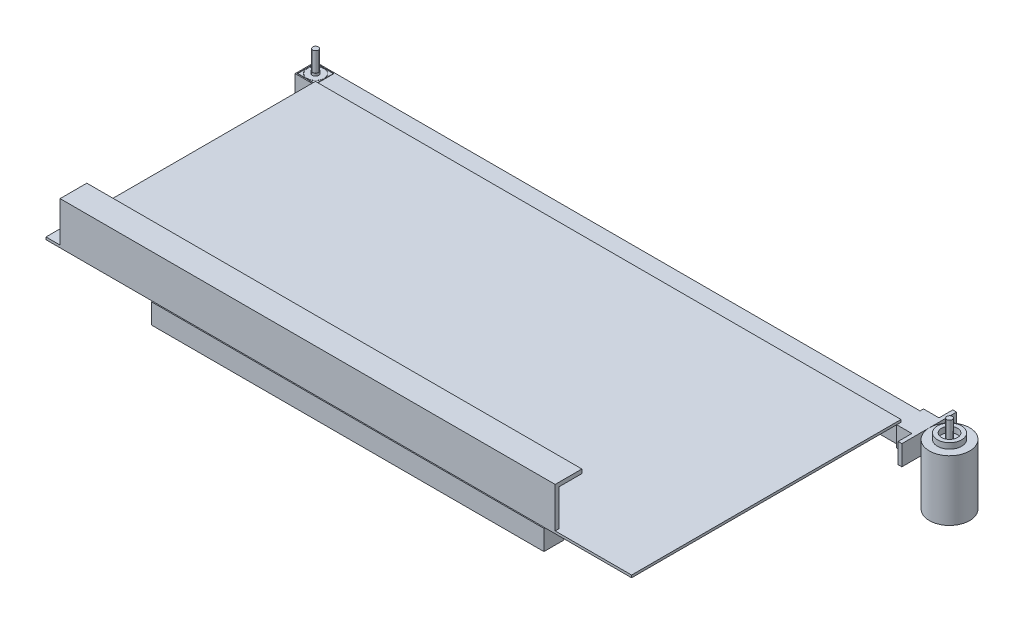
SolidWorks part; units mm, degrees
ref_plane "Front Plane" through (0, 0, 0) normal (0, 0, 1) x (1, 0, 0)
ref_plane "Top Plane" through (0, 0, 0) normal (0, 1, 0) x (1, 0, 0)
ref_plane "Right Plane" through (0, 0, 0) normal (1, 0, 0) x (0, 0, -1)
sketch "Sketch1" plane through (0, 0, 0) normal (0, 1, 0) x (1, 0, 0)
  line L0 (-360.5072, 0) -> (389.4928, 0)
  line L1 (389.4928, 0) -> (389.4928, -25)
  line L2 (389.4928, -25) -> (189.4928, -25)
  line L3 (189.4928, -25) -> (189.4928, -335)
  line L4 (189.4928, -335) -> (258.3333, -335)
  line L5 (258.3333, -335) -> (258.3333, -360)
  line L6 (258.3333, -360) -> (-229.3478, -360)
  line L7 (-229.3478, -360) -> (-229.3478, -335)
  line L8 (-229.3478, -335) -> (-160.5072, -335)
  line L9 (-160.5072, -335) -> (-160.5072, -25)
  line L10 (-160.5072, -25) -> (-360.5072, -25)
  line L11 (-360.5072, -25) -> (-360.5072, 0)
  line L12 (-135.5072, -25) -> (164.4928, -25)
  line L13 (164.4928, -25) -> (164.4928, -335)
  line L14 (164.4928, -335) -> (-135.5072, -335)
  line L15 (-135.5072, -335) -> (-135.5072, -25)
  dimension "D1" = 750
  dimension "D2" = 200
  dimension "D3" = 300
  dimension "D4" = 25
  dimension "D5" = 25
  dimension "D6" = 25
  dimension "D7" = 310
extrude "Boss-Extrude1" add sketch "Sketch1" along normal blind 25 contours L9 L10 L11 L0 L1 L2 L3 L4 L5 L6 L7 L8
sketch "Sketch4" plane through (-360.5072, 0, 0) normal (-1, 0, 0) x (0, 0, 1)
  line L1 (0, 25) -> (25.1974, 25)
  line L2 (0, 25) -> (0, -19.8582)
  line L3 (0, -19.8582) -> (25.1974, -19.8582)
  line L4 (25.1974, 25) -> (25.1974, -19.8582)
extrude "Boss-Extrude2" add sketch "Sketch4" along normal blind 25
sketch "Sketch5" plane through (0, 25, 0) normal (0, 1, 0) x (1, 0, 0)
  line L1 (-384.3095, -1.1004) -> (-361.3635, -1.1004)
  line L2 (-384.3095, -1.1004) -> (-384.3095, -23.8607)
  line L3 (-384.3095, -23.8607) -> (-361.3635, -23.8607)
  line L4 (-361.3635, -1.1004) -> (-361.3635, -23.8607)
extrude "Cut-Extrude1" cut sketch "Sketch5" against normal through all
sketch "Sketch7" plane through (0, 25, 0) normal (0, 1, 0) x (1, 0, 0)
  line L1 (-383.9453, -1.439) -> (-361.7536, -1.439)
  line L2 (-383.9453, -1.439) -> (-383.9453, -23.502)
  line L3 (-383.9453, -23.502) -> (-361.7536, -23.502)
  line L4 (-361.7536, -1.439) -> (-361.7536, -23.502)
extrude "Boss-Extrude4" add sketch "Sketch7" against normal blind 44 separate body
sketch "Sketch8" plane through (0, 25, 0) normal (0, 1, 0) x (1, 0, 0)
  line L0 (-384.3095, -1.1004) -> (-361.3635, -23.8607) construction
  circle A0 centre (-372.8365, -12.4805) radius 10.6558
extrude "Cut-Extrude2" cut sketch "Sketch8" against normal blind 8
sketch "Sketch9" plane through (0, -19, 0) normal (0, -1, 0) x (-1, 0, 0)
  line L0 (361.2767, -23.8809) -> (384.2478, -1.0919) construction
  circle A0 centre (372.7622, -12.4864) radius 10.6384
extrude "Cut-Extrude3" cut sketch "Sketch9" against normal blind 8
sketch "Sketch12" plane through (0, 17, 0) normal (0, 1, 0) x (1, 0, 0)
  line L0 (-361.3635, -1.1004) -> (-384.3095, -23.8607) construction
  circle A0 centre (-372.8365, -12.4805) radius 10.4586
  circle A1 centre (-372.8365, -12.4805) radius 4
  dimension "D1" = 8
extrude "Boss-Extrude5" add sketch "Sketch12" along normal through all and the other way through all
ref_plane "Plane1" through (0, 26, 0) normal (0, 1, 0) x (1, 0, 0)
sketch "Sketch14" plane through (0, 26, 0) normal (0, 1, 0) x (1, 0, 0)
  line L1 (-360.5072, -25) -> (366.97, -25)
  line L2 (-360.5072, -25) -> (-360.5072, -359.7131)
  line L3 (-360.5072, -359.7131) -> (366.97, -359.7131)
  line L4 (366.97, -25) -> (366.97, -359.7131)
extrude "Boss-Extrude6" add sketch "Sketch14" along normal blind 3 separate body
sketch "Sketch15" plane through (0, 0, 0) normal (1, 0, 0) x (0, 0, -1)
  line L0 (-359.7131, 29) -> (-359.7131, 79)
  line L1 (-359.7131, 79) -> (-326.5002, 79)
  line L2 (-326.5002, 79) -> (-326.5002, 74)
  line L3 (-326.5002, 74) -> (-354.7131, 74)
  line L4 (-354.7131, 74) -> (-354.7131, 29)
  line L5 (-354.7131, 29) -> (-359.7131, 29)
  dimension "D1" = 50
  dimension "D2" = 5
  dimension "D3" = 45
extrude "Boss-Extrude7" add sketch "Sketch15" along normal blind 272 and the other way blind 343
sketch "Sketch16" plane through (0, 25, 0) normal (0, 1, 0) x (1, 0, 0)
  circle A0 centre (-372.8365, -12.4805) radius 3.9261
extrude "Boss-Extrude8" add sketch "Sketch16" along normal blind 3 and the other way blind 54
sketch "Sketch17" plane through (0, 28, 0) normal (0, 1, 0) x (1, 0, 0)
  circle A2 centre (-372.8365, -12.4805) radius 3.45
  dimension "D1" = 6.9
extrude "Boss-Extrude9" add sketch "Sketch17" along normal blind 24
sketch "Sketch18" plane through (0, 25, 0) normal (0, 1, 0) x (1, 0, 0)
  line L0 (389.4928, -25) -> (389.4928, 0) construction
  circle A0 centre (414.4928, -12.2466) radius 25
  dimension "D1" = 50
extrude "Boss-Extrude10" add sketch "Sketch18" against normal blind 75 separate body
sketch "Sketch19" plane through (0, 25, 0) normal (0, 1, 0) x (1, 0, 0)
  line L0 (389.4928, 0) -> (389.4928, 21.4834)
  line L1 (389.4928, 21.4834) -> (384.8178, 21.4834)
  line L2 (384.8178, 21.4834) -> (384.8178, 4.3334)
  line L3 (384.8178, 4.3334) -> (365.5718, 4.3334)
  line L4 (365.5718, 4.3334) -> (365.5718, 0)
  line L5 (365.5718, 0) -> (389.4928, 0)
ref_plane "Plane2" through (0, 0, 12.5) normal (0, 0, 1) x (1, 0, 0)
extrude "Boss-Extrude12" add sketch "Sketch19" against normal blind 25
mirror "Mirror1" about plane through (0, 0, 12.5) normal (0, 0, 1) of "Boss-Extrude12"
sketch "Sketch21" plane through (0, 25, 0) normal (0, 1, 0) x (1, 0, 0)
  circle A0 centre (414.4928, -12.2466) radius 15
  circle A1 centre (414.4928, -12.2466) radius 10
  dimension "D1" = 30
  dimension "D2" = 20
extrude "Boss-Extrude13" add sketch "Sketch21" along normal blind 7
sketch "Sketch22" plane through (0, 25, 0) normal (0, 1, 0) x (1, 0, 0)
  circle A0 centre (414.4928, -12.2466) radius 3.45
  dimension "D1" = 6.9
extrude "Boss-Extrude14" add sketch "Sketch22" along normal blind 23
